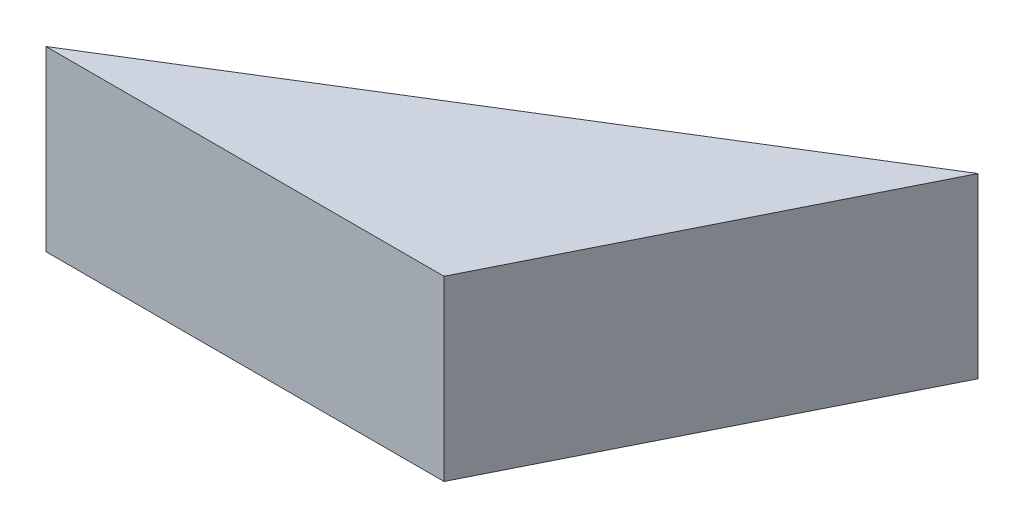
SolidWorks part; units mm, degrees
ref_plane "Front Plane" through (0, 0, 0) normal (0, 0, 1) x (1, 0, 0)
ref_plane "Top Plane" through (0, 0, 0) normal (0, 1, 0) x (1, 0, 0)
ref_plane "Right Plane" through (0, 0, 0) normal (1, 0, 0) x (0, 0, -1)
sketch "Sketch1" plane through (0, 0, 0) normal (0, 1, 0) x (1, 0, 0)
  line L0 (0, 0) -> (-13.4345, 0)
  line L1 (0, 0) -> (6.0091, 12.0157)
  line L2 (6.0091, 12.0157) -> (-13.4345, 0)
extrude "Boss-Extrude1" add sketch "Sketch1" along normal blind 6 contours L1 L2 L0
